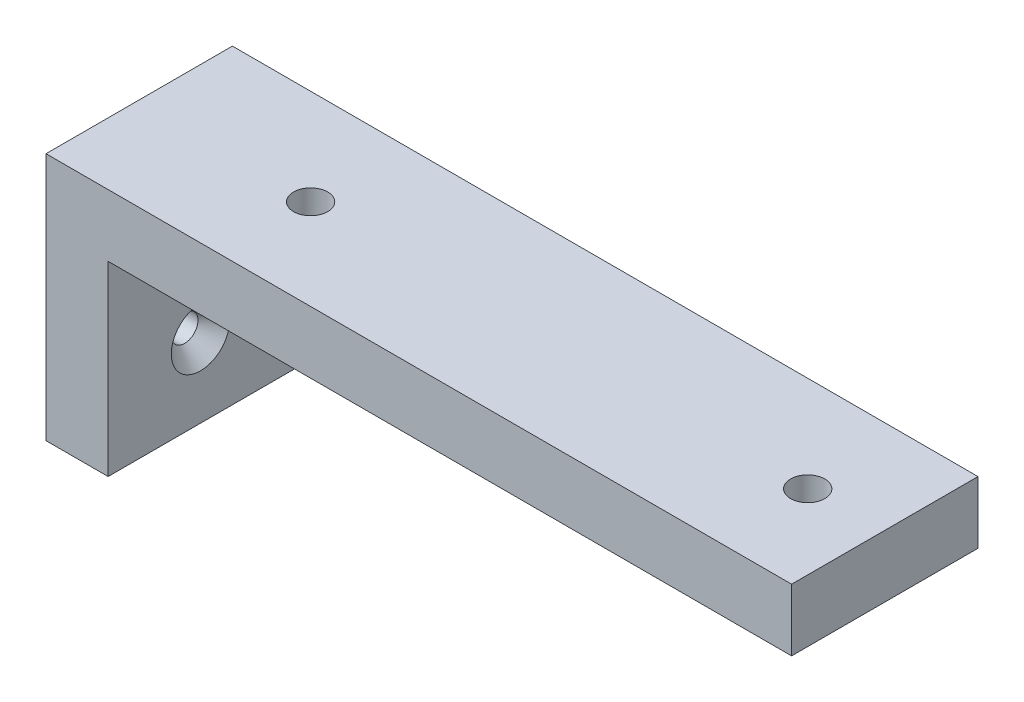
SolidWorks part; units mm, degrees
ref_plane "Front Plane" through (0, 0, 0) normal (0, 0, 1) x (1, 0, 0)
ref_plane "Top Plane" through (0, 0, 0) normal (0, 1, 0) x (1, 0, 0)
ref_plane "Right Plane" through (0, 0, 0) normal (1, 0, 0) x (0, 0, -1)
sketch "Sketch1" plane through (0, 0, 0) normal (0, 0, 1) x (1, 0, 0)
  line L0 (0, 0) -> (0, 40)
  line L1 (0, 40) -> (120, 40)
  line L2 (120, 40) -> (120, 30)
  line L3 (120, 30) -> (10, 30)
  line L4 (10, 30) -> (10, 0)
  line L5 (10, 0) -> (0, 0)
  dimension "D1" = 40
  dimension "D2" = 10
  dimension "D3" = 10
  dimension "D4" = 120
extrude "Boss-Extrude1" add sketch "Sketch1" along normal blind 30
hole_wizard "CBORE for M5 Hex Head Bolt1" positions "Sketch3" profile "Sketch4" counterbore size "M5" standard "ISO" end condition through all
sketch "Sketch3" plane through (0, 30, 0) normal (0, -1, 0) x (-1, 0, 0)
  line L0 (-120, -30) -> (-120, 0) construction
  point P0 (-108, -15.4101)
  point P2 (-28, -15.4101)
  dimension "D1" = 12
  dimension "D2" = 80
sketch "Sketch4" plane through (108, 30, 15.4101) normal (1, 0, 0) x (0, 0, -1)
  line L0 (0, 0) -> (0, 10)
  line L1 (0, 10) -> (2.75, 10)
  line L3 (2.75, 10) -> (2.75, 3.5)
  line L4 (2.75, 3.5) -> (6.119, 3.5)
  line L5 (6.119, 3.5) -> (6.119, 0)
  line L7 (6.119, 0) -> (0, 0)
  line L11 (0, -6.35) -> (0, 107.95) construction
  dimension "Thru Hole Dia." = 5.5
  dimension "Thru Hole Depth" = 10
  dimension "C'Bore Dia." = 12.238
  dimension "C'Bore Depth" = 3.5
hole_wizard "CSK for M4 Countersunk Raised Head Screw1" positions "Sketch6" profile "Sketch7" countersink size "M4" standard "ISO" end condition through all
sketch "Sketch6" plane through (10, 0, 0) normal (1, 0, 0) x (0, 0, -1)
  line L0 (-30, 0) -> (0, 0) construction
  point P0 (-15.1378, 12)
  dimension "D1" = 12
sketch "Sketch7" plane through (10, 12, 15.1378) normal (0, 1, 0) x (0, 0, -1)
  line L0 (0, 0) -> (0, 10)
  line L1 (0, 10) -> (2.15, 10)
  line L2 (2.15, 10) -> (2.15, 2.55)
  line L3 (2.15, 2.55) -> (4.7, 0)
  line L5 (4.7, 0) -> (0, 0)
  line L6 (-2.15, 2.55) -> (-4.7, 0) construction
  line L11 (0, -6.35) -> (0, 107.95) construction
  dimension "Thru Hole Dia." = 4.3
  dimension "Thru Hole Depth" = 10
  dimension "Near C'Sink Dia." = 9.4
  dimension "Near C'Sink Angle" = 90
